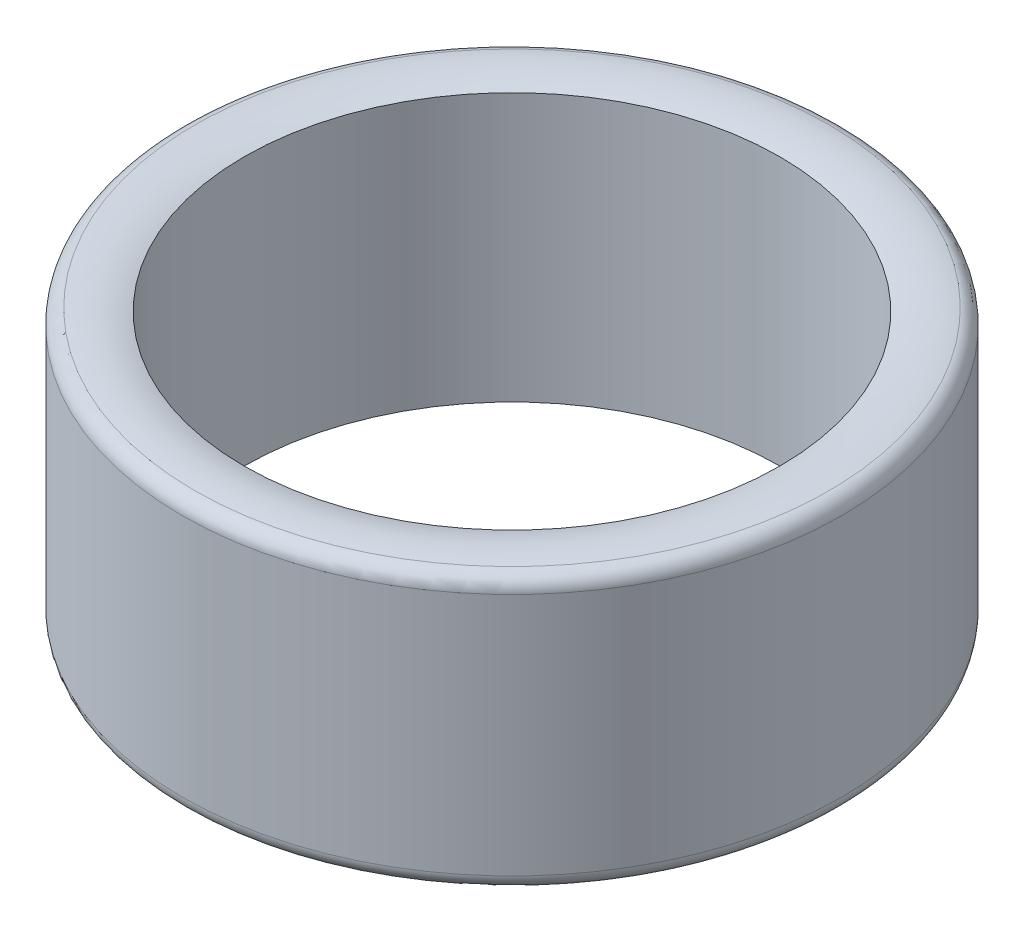
SolidWorks part; units mm, degrees
material "聚亚安酯(11671)"
ref_plane "前视基准面" through (0, 0, 0) normal (0, 0, 1) x (1, 0, 0)
ref_plane "上视基准面" through (0, 0, 0) normal (0, 1, 0) x (1, 0, 0)
ref_plane "右视基准面" through (0, 0, 0) normal (1, 0, 0) x (0, 0, -1)
sketch "草图1" plane through (0, 0, 0) normal (0, 1, 0) x (1, 0, 0)
  circle A0 centre (0, 0) radius 32
  circle A1 centre (0, 0) radius 26
  dimension "D1" = 64
  dimension "D2" = 52
extrude "凸台-拉伸1" add sketch "草图1" along normal mid plane 26
sketch "草图2" plane through (0, 0, 0) normal (0, 0, 1) x (1, 0, 0)
  line L0 (-26, 13) -> (-32, 13) construction
  line L1 (-32, 13) -> (-26, 13)
  line L2 (0, 0) -> (0, 18.0143) construction
  arc A0 (-26, 13) -> (-32, 13) centre (-29, 3.4606) ccw
  dimension "D1" = 10
revolve "旋转1" add sketch "草图2" angle 360 about L2
mirror "镜向1" about plane through (0, 0, 0) normal (0, 1, 0) of "旋转1"
fillet "圆角1" radius 1.5 2 edges at (0, -13, -32) (0, 13, 32)
